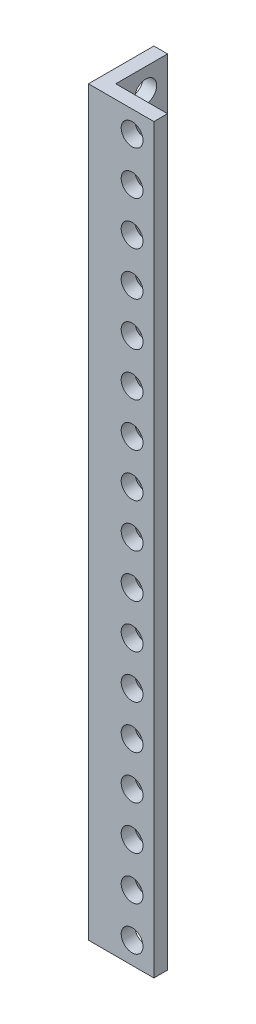
SolidWorks part; units mm, degrees
ref_plane "Front" through (0, 0, 0) normal (0, 0, 1) x (1, 0, 0)
ref_plane "Top" through (0, 0, 0) normal (0, 1, 0) x (1, 0, 0)
ref_plane "Right" through (0, 0, 0) normal (1, 0, 0) x (0, 0, -1)
ref_plane "Plane1" through (0, 0, 0) normal (-1, 0, 0) x (0, -1, 0)
sketch "Sketch1" plane through (0, 0, 0) normal (-1, 0, 0) x (0, -1, 0)
  line L0 (-136, 0) -> (-136, -12)
  line L1 (-136, -12) -> (0, -12)
  line L2 (0, -12) -> (0, 0)
  line L3 (0, 0) -> (-136, 0)
extrude "Boss-Extrude1" add sketch "Sketch1" against normal blind 12
sketch "Sketch2" plane through (0, 0, 0) normal (0, -1, 0) x (1, 0, 0)
  line L0 (2.5, -2.5) -> (2.5, -12)
  line L1 (2.5, -12) -> (12, -12)
  line L2 (12, -12) -> (12, -2.5)
  line L3 (12, -2.5) -> (2.5, -2.5)
extrude "Cut-Extrude1" cut sketch "Sketch2" against normal through all
hole_wizard "Ø4.0 (4) Diameter Hole1" positions "Sketch4" profile "Sketch3" hole size "Ø4.0" standard "ANSI Metric"
sketch "Sketch4" plane through (0, 0, -2.5) normal (0, 0, -1) x (-1, 0, 0)
  point P0 (-8, 4)
  point P1 (-8, 12)
  point P2 (-8, 20)
  point P3 (-8, 28)
  point P4 (-8, 36)
  point P5 (-8, 44)
  point P6 (-8, 52)
  point P7 (-8, 60)
  point P8 (-8, 68)
  point P9 (-8, 76)
  point P10 (-8, 84)
  point P11 (-8, 92)
  point P12 (-8, 100)
  point P13 (-8, 108)
  point P14 (-8, 116)
  point P15 (-8, 124)
  point P16 (-8, 132)
sketch "Sketch3" plane through (8, 4, -2.5) normal (1, 0, 0) x (0, 1, 0)
  line L0 (0, 0) -> (0, 2.5)
  line L1 (0, 2.5) -> (2, 2.5)
  line L2 (2, 2.5) -> (2, 0)
  line L5 (2, 0) -> (0, 0)
  line L11 (0, -6.35) -> (0, 107.95) construction
  dimension "Thru Hole Dia." = 4
  dimension "Thru Hole Depth" = 2.5
hole_wizard "Ø4.0 (4) Diameter Hole2" positions "Sketch6" profile "Sketch5" hole size "Ø4.0" standard "ANSI Metric"
sketch "Sketch6" plane through (2.5, 0, 0) normal (1, 0, 0) x (0, 0, -1)
  point P0 (8, 12)
  point P1 (8, 4)
  point P2 (8, 20)
  point P3 (8, 28)
  point P4 (8, 36)
  point P5 (8, 44)
  point P6 (8, 52)
  point P7 (8, 60)
  point P8 (8, 68)
  point P9 (8, 76)
  point P10 (8, 84)
  point P11 (8, 92)
  point P12 (8, 100)
  point P13 (8, 108)
  point P14 (8, 116)
  point P15 (8, 124)
  point P16 (8, 132)
sketch "Sketch5" plane through (2.5, 12, -8) normal (0, 1, 0) x (0, 0, -1)
  line L0 (0, 0) -> (0, 2.5)
  line L1 (0, 2.5) -> (2, 2.5)
  line L2 (2, 2.5) -> (2, 0)
  line L5 (2, 0) -> (0, 0)
  line L11 (0, -6.35) -> (0, 107.95) construction
  dimension "Thru Hole Dia." = 4
  dimension "Thru Hole Depth" = 2.5
